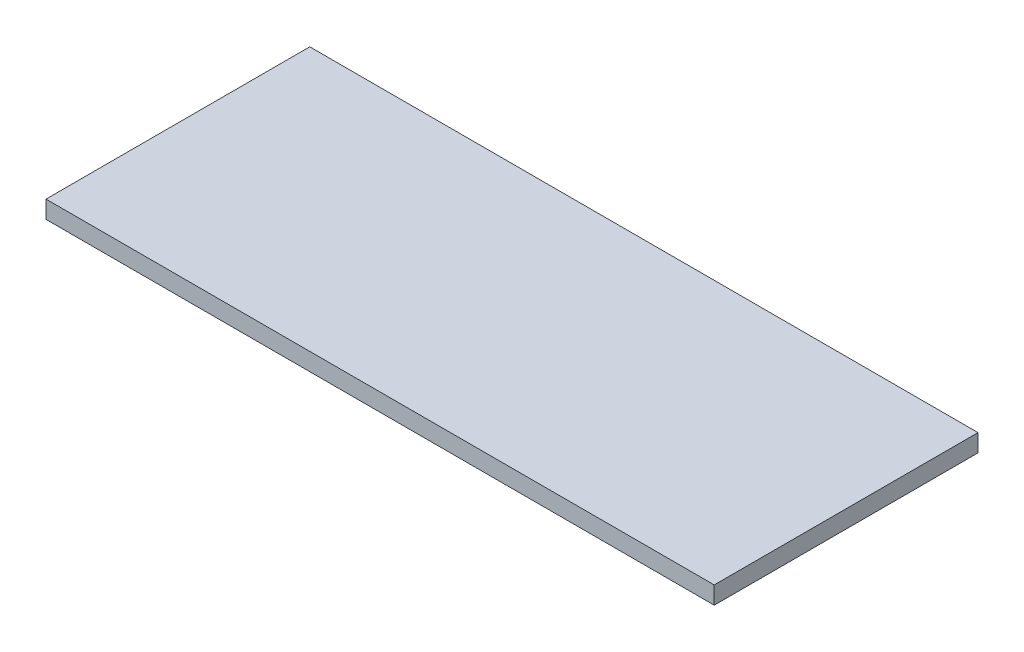
SolidWorks part; units mm, degrees
ref_plane "Front Plane" through (0, 0, 0) normal (0, 0, 1) x (1, 0, 0)
ref_plane "Top Plane" through (0, 0, 0) normal (0, 1, 0) x (1, 0, 0)
ref_plane "Right Plane" through (0, 0, 0) normal (1, 0, 0) x (0, 0, -1)
sketch "Sketch1" plane through (0, 0, 0) normal (0, 1, 0) x (1, 0, 0)
  line L1 (-190, -75) -> (190, -75)
  line L2 (-190, -75) -> (-190, 75)
  line L3 (-190, 75) -> (190, 75)
  line L4 (190, -75) -> (190, 75)
  line L5 (-190, -75) -> (190, 75) construction
  line L6 (-190, 75) -> (190, -75) construction
  point P0 (0, 0)
  dimension "D1" = 150
  dimension "D2" = 380
extrude "Boss-Extrude1" add sketch "Sketch1" along normal blind 10
